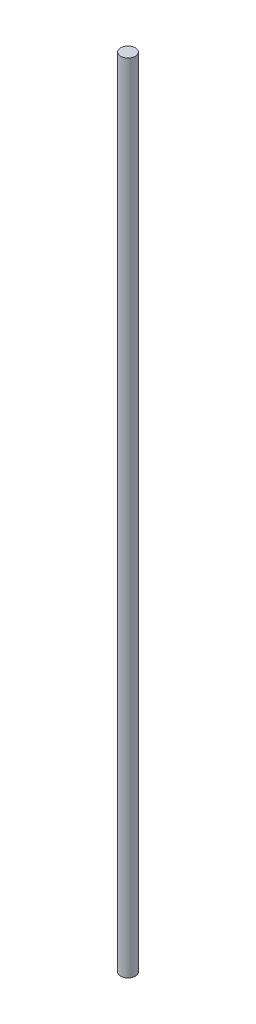
SolidWorks part; units mm, degrees
ref_plane "Front Plane" through (0, 0, 0) normal (0, 0, 1) x (1, 0, 0)
ref_plane "Top Plane" through (0, 0, 0) normal (0, 1, 0) x (1, 0, 0)
ref_plane "Right Plane" through (0, 0, 0) normal (1, 0, 0) x (0, 0, -1)
sketch "Sketch1" plane through (0, 0, 0) normal (0, 0, 1) x (1, 0, 0)
  line L0 (0, 5487.1805) -> (0, -5810.6354) construction
  line L1 (6, -5160.6354) -> (6, -5810.6354)
  line L2 (6, -5810.6354) -> (0, -5810.6354)
  line L3 (6, -5160.6354) -> (0, -5160.6354)
  dimension "D1" = 6
  dimension "D2" = 650
revolve "Revolve-Thin1" add sketch "Sketch1" angle 360 about L0
